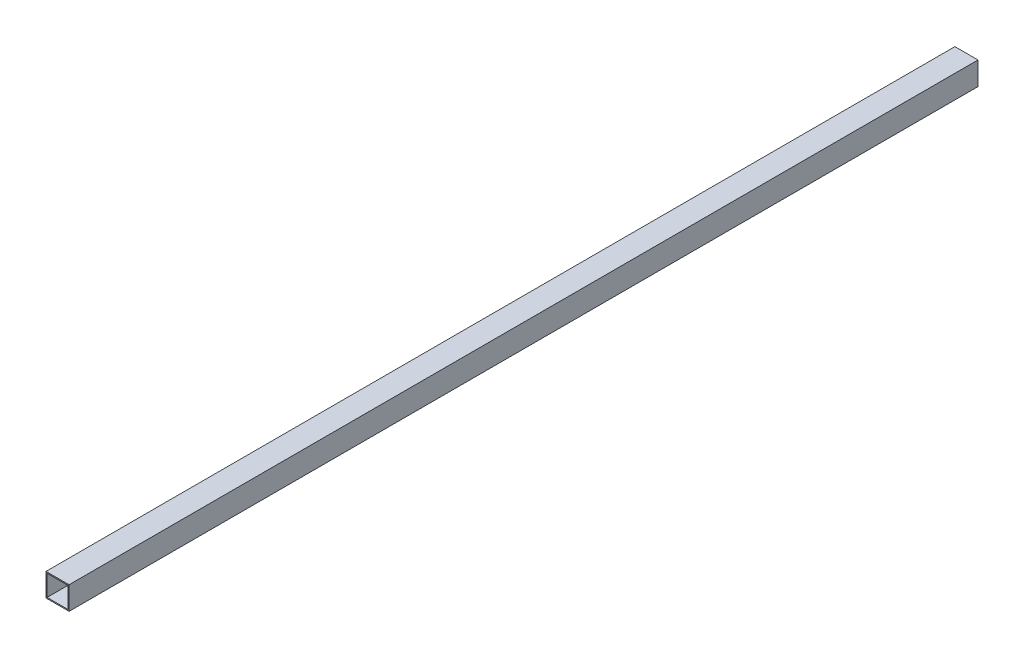
SolidWorks part; units mm, degrees
ref_plane "Front Plane" through (0, 0, 0) normal (0, 0, 1) x (1, 0, 0)
ref_plane "Top Plane" through (0, 0, 0) normal (0, 1, 0) x (1, 0, 0)
ref_plane "Right Plane" through (0, 0, 0) normal (1, 0, 0) x (0, 0, -1)
sketch "Sketch1" plane through (0, 0, 0) normal (0, 0, 1) x (1, 0, 0)
  line L0 (-11.5, 11.5) -> (-11.5, -11.5)
  line L1 (12.7, 12.7) -> (-12.7, 12.7)
  line L2 (12.7, 12.7) -> (12.7, -12.7)
  line L3 (12.7, -12.7) -> (-12.7, -12.7)
  line L4 (-12.7, 12.7) -> (-12.7, -12.7)
  line L5 (12.7, 12.7) -> (-12.7, -12.7) construction
  line L6 (12.7, -12.7) -> (-12.7, 12.7) construction
  line L7 (11.5, -11.5) -> (-11.5, -11.5)
  line L8 (11.5, 11.5) -> (11.5, -11.5)
  line L9 (11.5, 11.5) -> (-11.5, 11.5)
  point P0 (0, 0)
  dimension "D1" = 25.4
  dimension "D2" = 1.2
extrude "Boss-Extrude1" add sketch "Sketch1" along normal mid plane 1000
